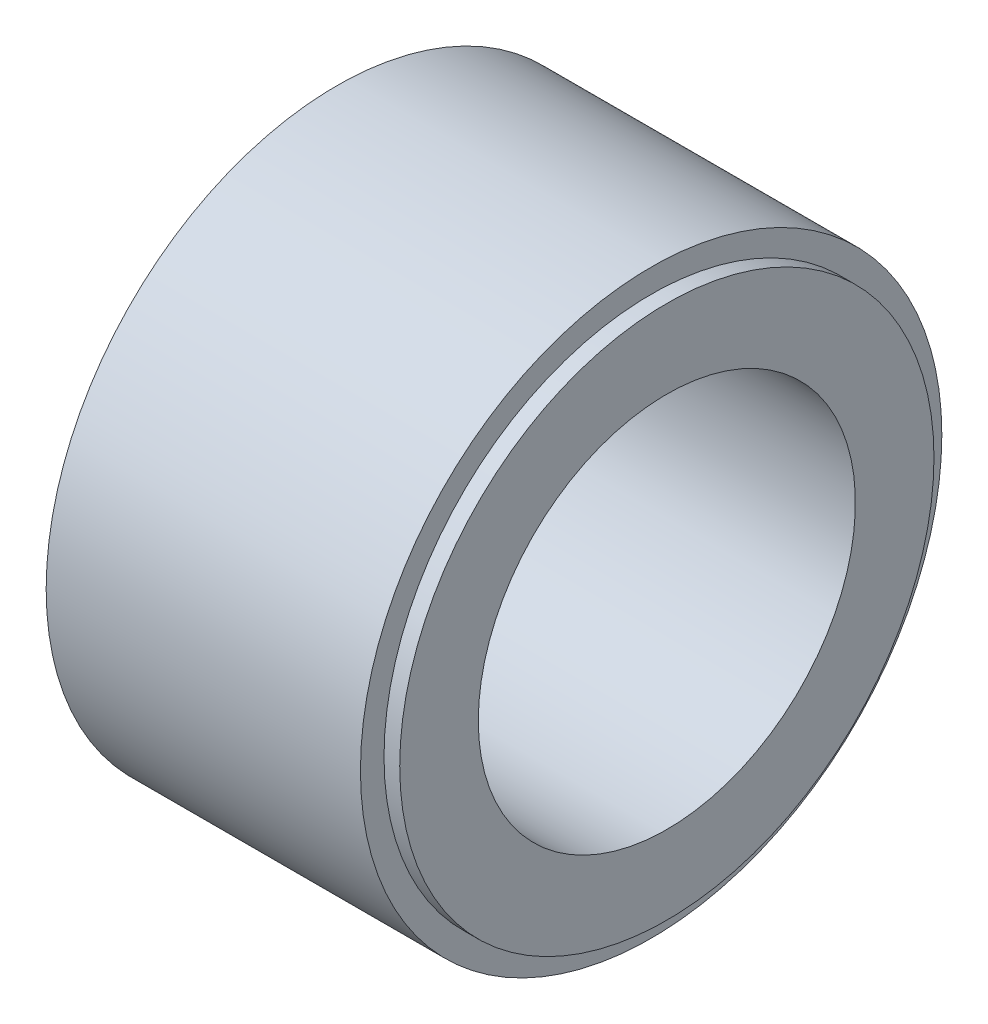
SolidWorks part; units mm, degrees
ref_plane "Front Plane" through (0, 0, 0) normal (0, 0, 1) x (1, 0, 0)
ref_plane "Top Plane" through (0, 0, 0) normal (0, 1, 0) x (1, 0, 0)
ref_plane "Right Plane" through (0, 0, 0) normal (1, 0, 0) x (0, 0, -1)
sketch "Sketch1" plane through (0, 0, 0) normal (0, 0, 1) x (1, 0, 0)
  line L0 (0, 0) -> (44, 0) construction
  line L1 (0, 24) -> (0, 34)
  line L2 (0, 34) -> (2, 34)
  line L3 (2, 34) -> (2, 30)
  line L4 (2, 30) -> (42, 30)
  line L5 (42, 30) -> (42, 34)
  line L6 (42, 34) -> (44, 34)
  line L7 (44, 34) -> (44, 24)
  line L8 (0, 0) -> (44, 0) construction
  line L9 (0, 24) -> (44, 24)
  point P5 (1, 34)
  dimension "D1" = 44
  dimension "D2" = 40
  dimension "D3" = 34
  dimension "D4" = 4
  dimension "D5" = 10
revolve "Revolve2" add sketch "Sketch1" angle 360 about L0
sketch "Sketch2" plane through (0, 0, 0) normal (0, 0, 1) x (1, 0, 0)
  line L0 (2, 34) -> (2, 30) construction
  line L1 (42, 30) -> (42, 34) construction
  line L2 (2, 30) -> (42, 30) construction
  line L3 (2, 34) -> (2, 30)
  line L4 (42, 30) -> (42, 34)
  line L5 (2, 30) -> (42, 30)
  line L6 (2, 34) -> (2, 37)
  line L7 (2, 37) -> (42, 37)
  line L8 (42, 37) -> (42, 34)
  line L9 (0, 0) -> (44, 0) construction
  dimension "D1" = 37
revolve "Revolve3" add sketch "Sketch2" angle 360 about L0
sketch "Sketch3" plane through (0, 0, 0) normal (-1, 0, 0) x (0, 0, 1)
  circle A0 centre (0, 0) radius 24 construction
  circle A1 centre (0, 0) radius 24
  circle A2 centre (19, 0) radius 4
  circle A3 centre (0, 0) radius 3
  circle A4 centre (9.5, -16.4545) radius 4
  circle A5 centre (-9.5, -16.4545) radius 4
  circle A6 centre (-19, 0) radius 4
  circle A7 centre (-9.5, 16.4545) radius 4
  circle A8 centre (9.5, 16.4545) radius 4
  point P18 (0, 0)
  dimension "D2" = 8
  dimension "D3" = 6
  dimension "D1" = 19
  dimension "D4" = 6
extrude "Boss-Extrude1" add sketch "Sketch3" against normal blind 4
